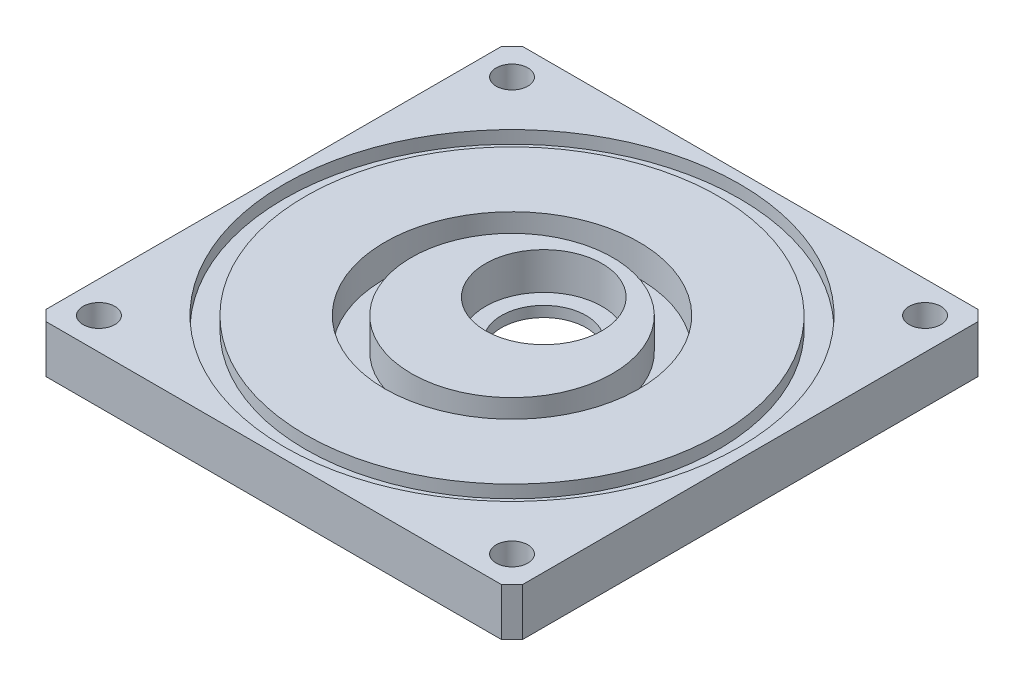
SolidWorks part; units mm, degrees
ref_plane "前视基准面" through (0, 0, 0) normal (0, 0, 1) x (1, 0, 0)
ref_plane "上视基准面" through (0, 0, 0) normal (0, 1, 0) x (1, 0, 0)
ref_plane "右视基准面" through (0, 0, 0) normal (1, 0, 0) x (0, 0, -1)
sketch "草图1" plane through (0, 0, 0) normal (0, 1, 0) x (1, 0, 0)
  line L1 (-22.5, -22.5) -> (22.5, -22.5)
  line L2 (-22.5, -22.5) -> (-22.5, 22.5)
  line L3 (-22.5, 22.5) -> (22.5, 22.5)
  line L4 (22.5, -22.5) -> (22.5, 22.5)
  line L5 (-22.5, -22.5) -> (22.5, 22.5) construction
  line L6 (-22.5, 22.5) -> (22.5, -22.5) construction
  point P0 (0, 0)
  dimension "D1" = 45
  dimension "D2" = 45
extrude "凸台-拉伸1" add sketch "草图1" along normal blind 4.5
sketch "草图2" plane through (0, 4.5, 0) normal (0, 1, 0) x (1, 0, 0)
  line L0 (0, 0) -> (0, 3) construction
  circle A0 centre (0, 3) radius 5.5
  dimension "D2" = 11
  dimension "D1" = 3
extrude "切除-拉伸1" cut sketch "草图2" against normal blind 3.5
sketch "草图3" plane through (0, 1, 0) normal (0, 1, 0) x (1, 0, 0)
  circle A0 centre (0, 3) radius 4
  dimension "D1" = 8
extrude "切除-拉伸2" cut sketch "草图3" against normal through all
sketch "草图4" plane through (0, 4.5, 0) normal (0, 1, 0) x (1, 0, 0)
  circle A0 centre (0, 0) radius 9.5
  circle A1 centre (0, 0) radius 12
  dimension "D1" = 19
  dimension "D2" = 24
extrude "切除-拉伸3" cut sketch "草图4" against normal blind 3
sketch "草图5" plane through (0, 4.5, 0) normal (0, 1, 0) x (1, 0, 0)
  circle A0 centre (0, 0) radius 19.5
  circle A1 centre (0, 0) radius 21.5
  dimension "D1" = 43
  dimension "D2" = 39
extrude "切除-拉伸4" cut sketch "草图5" against normal blind 1.2
chamfer "倒角1" distance 1 angle 45 4 edges at (-22.5, 2.25, 22.5) (22.5, 2.25, 22.5) (22.5, 2.25, -22.5) (-22.5, 2.25, -22.5)
sketch "草图6" plane through (0, 0, 0) normal (0, -1, 0) x (1, 0, 0)
  line L0 (0, 22.5) -> (0, -22.5) construction
  line L1 (-21.5, 22.5) -> (21.5, 22.5) construction
  line L2 (21.5, -22.5) -> (-21.5, -22.5) construction
  line L3 (-22.5, 0) -> (22.5, 0) construction
  line L4 (-22.5, -21.5) -> (-22.5, 21.5) construction
  line L5 (22.5, 21.5) -> (22.5, -21.5) construction
  circle A0 centre (-19.5, 19.5) radius 1.5
  circle A1 centre (19.5, 19.5) radius 1.5
  circle A2 centre (19.5, -19.5) radius 1.5
  circle A3 centre (-19.5, -19.5) radius 1.5
  dimension "D1" = 3
  dimension "D2" = 3
  dimension "D3" = 3
extrude "切除-拉伸5" cut sketch "草图6" against normal through all
